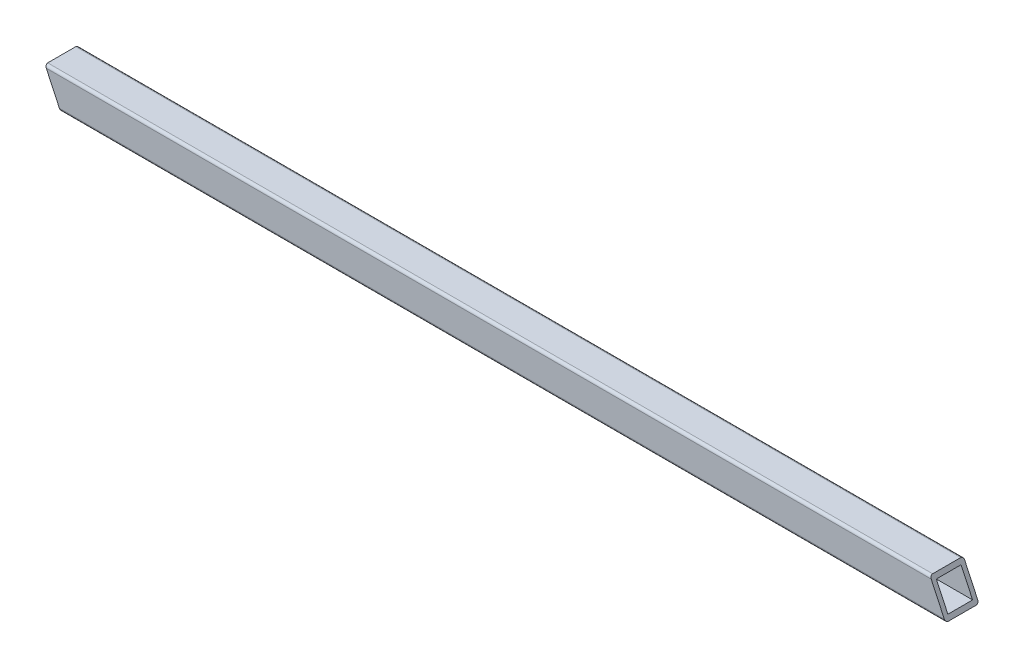
SolidWorks part; units mm, degrees
material "Plain Carbon Steel"
ref_plane "Front Plane" through (0, 0, 0) normal (0, 0, 1) x (1, 0, 0)
ref_plane "Top Plane" through (0, 0, 0) normal (0, 1, 0) x (1, 0, 0)
ref_plane "Right Plane" through (0, 0, 0) normal (1, 0, 0) x (0, 0, -1)
sketch "Sketch1" plane through (0, 0, 0) normal (1, 0, 0) x (0, 0, -1)
  line L0 (0, 2.54) -> (0, 29.21)
  line L1 (-2.54, 31.75) -> (-29.21, 31.75)
  line L2 (-31.75, 29.21) -> (-31.75, 2.54)
  line L3 (-29.21, 0) -> (-2.54, 0)
  line L4 (-4.1275, 4.1275) -> (-4.1275, 27.6225)
  line L5 (-4.1275, 27.6225) -> (-27.6225, 27.6225)
  line L6 (-27.6225, 27.6225) -> (-27.6225, 4.1275)
  line L7 (-27.6225, 4.1275) -> (-4.1275, 4.1275)
  arc A0 (-31.75, 2.54) -> (-29.21, 0) centre (-29.21, 2.54) ccw
  arc A1 (0, 2.54) -> (-2.54, 0) centre (-2.54, 2.54) cw
  arc A2 (0, 29.21) -> (-2.54, 31.75) centre (-2.54, 29.21) ccw
  arc A3 (-31.75, 29.21) -> (-29.21, 31.75) centre (-29.21, 29.21) cw
  arc A4 (-4.1275, 27.6225) -> (-4.1275, 27.6225) centre (-4.1275, 27.6225) ccw
  arc A5 (-27.6225, 27.6225) -> (-27.6225, 27.6225) centre (-27.6225, 27.6225) cw
  arc A6 (-27.6225, 4.1275) -> (-27.6225, 4.1275) centre (-27.6225, 4.1275) ccw
  arc A7 (-4.1275, 4.1275) -> (-4.1275, 4.1275) centre (-4.1275, 4.1275) cw
  point P12 (0, 0)
  point P15 (0, 31.75)
  point P18 (-31.75, 31.75)
  dimension "D3" = 2.54
  dimension "D1" = 31.75
  dimension "D2" = 31.75
  dimension "D4" = 4.1275
extrude "Boss-Extrude1" add sketch "Sketch1" along normal blind 342.2287
scale "Scale1" scale about centroid uniform scaling no x scale factor 1 y scale factor 0.4 z scale factor 0.4
sketch "Sketch2" plane through (0, 0, 22.225) normal (0, 0, 1) x (1, 0, 0)
  line L4 (342.2287, 9.525) -> (336.3066, 22.225)
  line L5 (342.2287, 22.225) -> (0, 22.225) construction
  line L6 (336.3066, 22.225) -> (342.2287, 22.225)
  line L7 (342.2287, 22.225) -> (342.2287, 9.525)
  line L8 (0, 9.525) -> (0, 22.225)
  line L9 (342.2287, 9.525) -> (0, 9.525) construction
  line L10 (0, 22.225) -> (0, 21.209) construction
  line L11 (0, 22.225) -> (5.9221, 9.525)
  line L12 (5.9221, 9.525) -> (0, 9.525)
  point P15 (5.6705, 9.525)
  point P17 (0, 22.225)
  dimension "D2" = 25
  dimension "D1" = 25
extrude "Cut-Extrude1" cut sketch "Sketch2" against normal through all
equation "\"D2@Sketch2\"=\"D1@Sketch2\""
